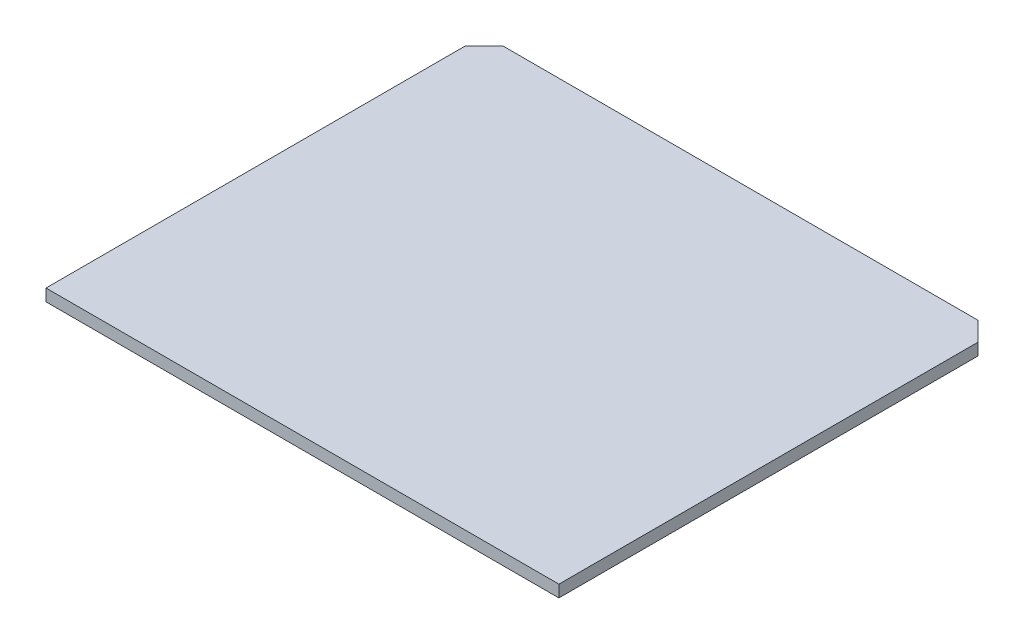
SolidWorks part; units mm, degrees
ref_plane "Front Plane" through (0, 0, 0) normal (0, 0, 1) x (1, 0, 0)
ref_plane "Top Plane" through (0, 0, 0) normal (0, 1, 0) x (1, 0, 0)
ref_plane "Right Plane" through (0, 0, 0) normal (1, 0, 0) x (0, 0, -1)
sketch "Sketch1" plane through (0, 0, 0) normal (0, 1, 0) x (1, 0, 0)
  line L1 (-34.29, 29.29) -> (34.29, 29.29)
  line L2 (-34.29, 29.29) -> (-34.29, -29.29)
  line L3 (-34.29, -29.29) -> (34.29, -29.29)
  line L4 (34.29, 29.29) -> (34.29, -29.29)
  line L5 (-34.29, 29.29) -> (34.29, -29.29) construction
  line L6 (-34.29, -29.29) -> (34.29, 29.29) construction
  point P0 (0, 0)
  dimension "D1" = 68.58
  dimension "D2" = 58.58
extrude "Boss-Extrude1" add sketch "Sketch1" along normal blind 1.6
chamfer "Chamfer1" distance 2.54 angle 45 2 edges at (34.29, 0.8, -29.29) (-34.29, 0.8, -29.29)
